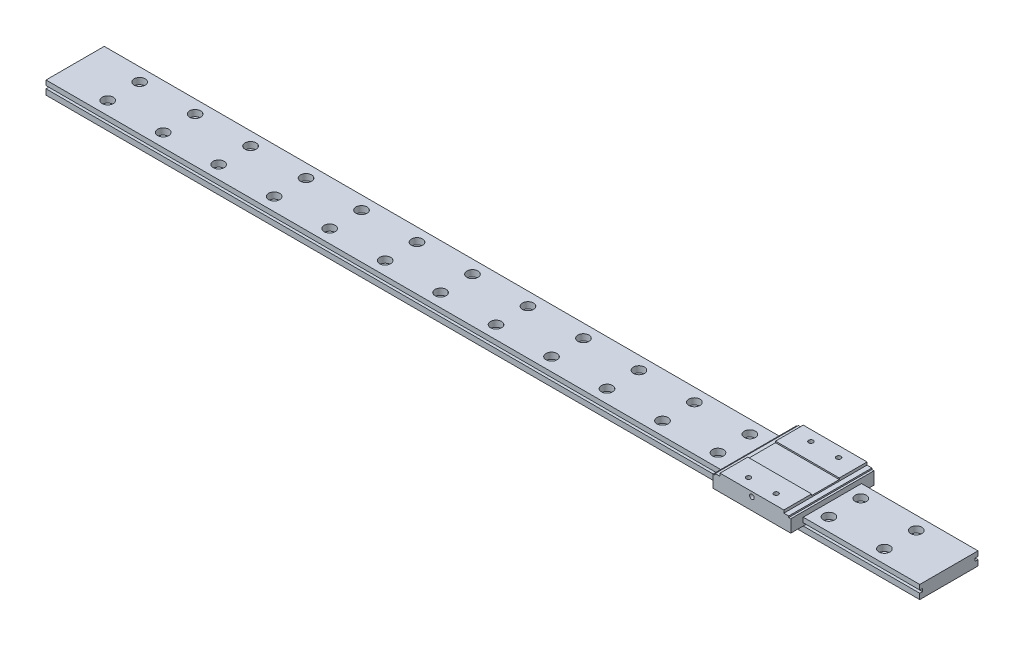
SolidWorks part; units mm, degrees
ref_plane "정면" through (0, 0, 0) normal (0, 0, 1) x (1, 0, 0)
ref_plane "윗면" through (0, 0, 0) normal (0, 1, 0) x (1, 0, 0)
ref_plane "우측면" through (0, 0, 0) normal (1, 0, 0) x (0, 0, -1)
sketch "스케치1" plane through (0, 0, 0) normal (0, 1, 0) x (1, 0, 0)
  line L1 (0, 0) -> (630, 0)
  line L2 (0, 0) -> (0, 42)
  line L3 (0, 42) -> (630, 42)
  line L4 (630, 0) -> (630, 42)
  dimension "D1" = 630
  dimension "D2" = 42
extrude "보스-돌출1" add sketch "스케치1" along normal blind 9.5
sketch "스케치2" plane through (0, 9.5, 0) normal (0, 1, 0) x (1, 0, 0)
  line L0 (0, 42) -> (0, 0) construction
  line L1 (0, 0) -> (630, 0) construction
  circle A0 centre (35, 32.5) radius 4
  circle A1 centre (35, 9.5) radius 4
  circle A2 centre (75, 32.5) radius 4
  circle A3 centre (75, 9.5) radius 4
  circle A4 centre (115, 32.5) radius 4
  circle A5 centre (115, 9.5) radius 4
  circle A6 centre (155, 32.5) radius 4
  circle A7 centre (155, 9.5) radius 4
  circle A8 centre (195, 32.5) radius 4
  circle A9 centre (195, 9.5) radius 4
  circle A10 centre (235, 32.5) radius 4
  circle A11 centre (235, 9.5) radius 4
  circle A12 centre (275, 32.5) radius 4
  circle A13 centre (275, 9.5) radius 4
  circle A14 centre (315, 32.5) radius 4
  circle A15 centre (315, 9.5) radius 4
  circle A16 centre (355, 32.5) radius 4
  circle A17 centre (355, 9.5) radius 4
  circle A18 centre (395, 32.5) radius 4
  circle A19 centre (395, 9.5) radius 4
  circle A20 centre (435, 32.5) radius 4
  circle A21 centre (435, 9.5) radius 4
  circle A22 centre (475, 32.5) radius 4
  circle A23 centre (475, 9.5) radius 4
  circle A24 centre (515, 32.5) radius 4
  circle A25 centre (515, 9.5) radius 4
  circle A26 centre (555, 32.5) radius 4
  circle A27 centre (555, 9.5) radius 4
  circle A28 centre (595, 32.5) radius 4
  circle A29 centre (595, 9.5) radius 4
  dimension "D4" = 8
  dimension "D1" = 35
  dimension "D2" = 23
  dimension "D3" = 9.5
  dimension "D5" = 15
extrude "컷-돌출1" cut sketch "스케치2" against normal blind 4.5
sketch "스케치3" plane through (0, 5, 0) normal (0, 1, 0) x (1, 0, 0)
  circle A0 centre (35, 32.5) radius 2.25
  circle A1 centre (35, 9.5) radius 2.25
  circle A2 centre (75, 32.5) radius 2.25
  circle A3 centre (75, 9.5) radius 2.25
  circle A4 centre (115, 32.5) radius 2.25
  circle A5 centre (115, 9.5) radius 2.25
  circle A6 centre (155, 32.5) radius 2.25
  circle A7 centre (155, 9.5) radius 2.25
  circle A8 centre (195, 32.5) radius 2.25
  circle A9 centre (195, 9.5) radius 2.25
  circle A10 centre (235, 32.5) radius 2.25
  circle A11 centre (235, 9.5) radius 2.25
  circle A12 centre (275, 32.5) radius 2.25
  circle A13 centre (275, 9.5) radius 2.25
  circle A14 centre (315, 32.5) radius 2.25
  circle A15 centre (315, 9.5) radius 2.25
  circle A16 centre (355, 32.5) radius 2.25
  circle A17 centre (355, 9.5) radius 2.25
  circle A18 centre (395, 32.5) radius 2.25
  circle A19 centre (395, 9.5) radius 2.25
  circle A20 centre (435, 32.5) radius 2.25
  circle A21 centre (435, 9.5) radius 2.25
  circle A22 centre (475, 32.5) radius 2.25
  circle A23 centre (475, 9.5) radius 2.25
  circle A24 centre (515, 32.5) radius 2.25
  circle A25 centre (515, 9.5) radius 2.25
  circle A26 centre (555, 32.5) radius 2.25
  circle A27 centre (555, 9.5) radius 2.25
  circle A28 centre (595, 32.5) radius 2.25
  circle A29 centre (595, 9.5) radius 2.25
  dimension "D1" = 4.5
  dimension "D2" = 15
extrude "컷-돌출2" cut sketch "스케치3" against normal through all
ref_plane "평면1" through (0, 4, 0) normal (0, -1, 0) x (-1, 0, 0)
sketch "스케치16" plane through (630, 0, 0) normal (1, 0, 0) x (0, 0, -1)
  line L0 (40, 5) -> (47.2012, 5) construction
  line L1 (-3.1442, 6) -> (2, 6)
  line L2 (-3.1442, 6) -> (-3.1442, 4)
  line L3 (-3.1442, 4) -> (2, 4)
  line L4 (2, 6) -> (2, 4)
  line L5 (40, 6) -> (47.2012, 6)
  line L6 (40, 6) -> (40, 4)
  line L7 (40, 4) -> (47.2012, 4)
  line L8 (47.2012, 6) -> (47.2012, 4)
  line L9 (0, 9.5) -> (0, 0) construction
  line L10 (42, 9.5) -> (42, 0) construction
  line L11 (21, 9.5) -> (21, 0) construction
  line L12 (0, 9.5) -> (42, 9.5) construction
  line L13 (0, 0) -> (42, 0) construction
  line L14 (-3.1442, 5) -> (2, 5) construction
  dimension "D1" = 2
  dimension "D2" = 4
  dimension "D3" = 2
  dimension "D4" = 2
extrude "컷-돌출6" cut sketch "스케치16" against normal through all
sketch "스케치6" plane through (0, 4, 0) normal (0, -1, 0) x (-1, 0, 0)
  line L0 (-630, 21) -> (18.216, 21) construction
  line L1 (-490, 51) -> (-546, 51)
  line L2 (-490, 51) -> (-490, -9)
  line L3 (-490, -9) -> (-546, -9)
  line L4 (-546, 51) -> (-546, -9)
  line L5 (-630, 0) -> (-630, 42) construction
  circle A0 centre (-555, 9.5) radius 4 construction
  dimension "D4" = 5
  dimension "D1" = 60
  dimension "D2" = 30
  dimension "D3" = 56
extrude "보스-돌출2" add sketch "스케치6" against normal blind 12
sketch "스케치7" plane through (0, 16, 0) normal (0, 1, 0) x (1, 0, 0)
  line L0 (490, 0) -> (490, 42) construction
  line L1 (546, 21) -> (490, 21) construction
  line L2 (546, 42) -> (546, 0) construction
  point P0 (508, 43.5)
  point P1 (528, 43.5)
  point P2 (508, -1.5)
  point P3 (528, -1.5)
  dimension "D1" = 18
  dimension "D2" = 20
  dimension "D3" = 45
  dimension "D4" = 22.5
hole_wizard "M4 나사 구멍1" positions "스케치7" profile "스케치8" tap size "M4" standard "ISO"
sketch "스케치8" plane through (508, 16, -43.5) normal (1, 0, 0) x (0, 0, 1)
  line L0 (0, 0) -> (0, 7.9914)
  line L1 (0, 7.9914) -> (1.65, 7)
  line L2 (1.65, 7) -> (1.65, 0)
  line L5 (1.65, 0) -> (0, 0)
  line L10 (0, 7.9914) -> (-1.65, 7) construction
  line L11 (0, -6.35) -> (0, 107.95) construction
  dimension "탭 드릴 지름" = 3.3
  dimension "탭 드릴 깊이" = 7
  dimension "드릴 각도" = 118
cosmetic thread "구멍 나사산1" parameters "D1"=4.5, "D2"=4
cosmetic thread "구멍 나사산2" parameters "D1"=4.5, "D2"=4
cosmetic thread "구멍 나사산3" parameters "D1"=4.5, "D2"=4
cosmetic thread "구멍 나사산4" parameters "D1"=4.5, "D2"=4
sketch "스케치9" plane through (0, 16, 0) normal (0, 1, 0) x (1, 0, 0)
  line L0 (546, -9) -> (490, -9) construction
  line L1 (490, 51) -> (495, 51)
  line L2 (490, 51) -> (490, -9)
  line L3 (490, -9) -> (495, -9)
  line L4 (495, 51) -> (495, -9)
  line L6 (546, 51) -> (541, 51)
  line L7 (546, 51) -> (546, -9)
  line L8 (546, -9) -> (541, -9)
  line L9 (541, 51) -> (541, -9)
  dimension "D1" = 5
  dimension "D2" = 5
extrude "컷-돌출3" cut sketch "스케치9" against normal blind 2
sketch "스케치10" plane through (0, 16, 0) normal (0, 1, 0) x (1, 0, 0)
  line L0 (495, -9) -> (495, 51) construction
  line L1 (495, 31) -> (541, 31)
  line L2 (495, 31) -> (495, 11)
  line L3 (495, 11) -> (541, 11)
  line L4 (541, 31) -> (541, 11)
  line L5 (541, 51) -> (541, -9) construction
  line L6 (495, 21) -> (541, 21) construction
  dimension "D1" = 20
extrude "컷-돌출4" cut sketch "스케치10" against normal blind 1
sketch "스케치11" plane through (0, 14, 0) normal (0, 1, 0) x (1, 0, 0)
  line L0 (541, -9) -> (546, -9) construction
  line L1 (546, 51) -> (544.5, 51)
  line L2 (546, 51) -> (546, -9)
  line L3 (546, -9) -> (544.5, -9)
  line L4 (544.5, 51) -> (544.5, -9)
  line L5 (490, -9) -> (495, -9) construction
  line L6 (490, 51) -> (491.5, 51)
  line L7 (490, 51) -> (490, -9)
  line L8 (490, -9) -> (491.5, -9)
  line L9 (491.5, 51) -> (491.5, -9)
  dimension "D1" = 1.5
  dimension "D2" = 1.5
extrude "컷-돌출5" cut sketch "스케치11" against normal blind 1
sketch "스케치14" plane through (0, 0, 9) normal (0, 0, 1) x (1, 0, 0)
  line L0 (541, 16) -> (495, 16) construction
  line L2 (490, 13) -> (490, 4) construction
  point P0 (518, 12.75)
  dimension "D1" = 3.25
  dimension "D2" = 28
hole_wizard "M4 나사 구멍2" positions "스케치14" profile "스케치13" tap size "M4" standard "ISO" end condition through all
sketch "스케치13" plane through (518, 12.75, 9) normal (1, 0, 0) x (0, -1, 0)
  line L0 (0, 0) -> (0, 60)
  line L1 (0, 60) -> (1.65, 60)
  line L2 (1.65, 60) -> (1.65, 0)
  line L5 (1.65, 0) -> (0, 0)
  line L11 (0, -6.35) -> (0, 107.95) construction
  dimension "관통 탭 드릴 지름" = 3.3
  dimension "관통 탭 드릴 깊이" = 60
cosmetic thread "구멍 나사산5" parameters "D2"=4
ref_plane "평면2" through (0, 0, -21) normal (0, 0, -1) x (-1, 0, 0)
